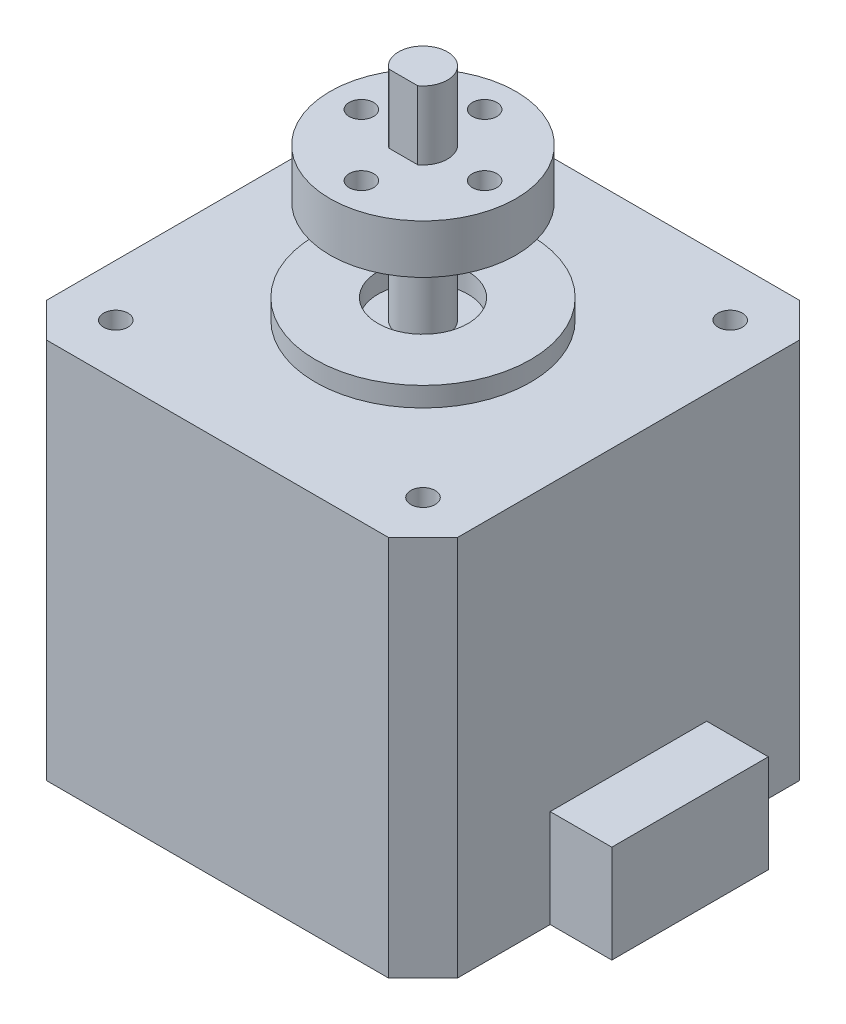
SolidWorks part; units mm, degrees
ref_plane "Plan de face" through (0, 0, 0) normal (0, 0, 1) x (1, 0, 0)
ref_plane "Plan de dessus" through (0, 0, 0) normal (0, 1, 0) x (1, 0, 0)
ref_plane "Plan de droite" through (0, 0, 0) normal (1, 0, 0) x (0, 0, -1)
sketch "Esquisse1" plane through (0, 0, 0) normal (0, 1, 0) x (1, 0, 0)
  line L0 (3.5355, 2.5496) -> (0, 6.0851)
  line L1 (0, 6.0851) -> (0, 41.014)
  line L2 (0, 41.014) -> (3.5355, 44.5496)
  line L3 (3.5355, 44.5496) -> (38.4645, 44.5496)
  line L4 (38.4645, 44.5496) -> (42, 41.014)
  line L5 (42, 41.014) -> (42, 6.0851)
  line L6 (42, 6.0851) -> (38.4645, 2.5496)
  line L7 (38.4645, 2.5496) -> (3.5355, 2.5496)
  dimension "D1" = 42
  dimension "D2" = 42
  dimension "D3" = 5
  dimension "D4" = 5
  dimension "D5" = 5
  dimension "D6" = 5
  dimension "D7" = 135
extrude "Boss.-Extru.1" add sketch "Esquisse1" along normal blind 39
sketch "Esquisse2" plane through (0, 39, 0) normal (0, 1, 0) x (1, 0, 0)
  line L1 (38.4645, 44.5496) -> (3.5355, 44.5496) construction
  line L2 (0, 41.014) -> (0, 6.0851) construction
  line L4 (42, 6.0851) -> (42, 41.014) construction
  line L5 (3.5355, 2.5496) -> (38.4645, 2.5496) construction
  circle A0 centre (5.3, 39.2496) radius 1.25
  circle A1 centre (36.7, 39.2496) radius 1.25
  circle A2 centre (36.7, 7.8496) radius 1.25
  circle A3 centre (5.3, 7.8496) radius 1.25
  dimension "D1" = 2.5
  dimension "D4" = 2.5
  dimension "D6" = 2.5
  dimension "D8" = 2.5
  dimension "D2" = 5.3
  dimension "D3" = 5.3
  dimension "D5" = 5.3
  dimension "D7" = 5.3
extrude "Enlèv. mat.-Extru.1" cut sketch "Esquisse2" against normal blind 39
sketch "Esquisse3" plane through (0, 39, 0) normal (0, 1, 0) x (1, 0, 0)
  line L0 (5.3, 7.8496) -> (36.7, 39.2496) construction
  line L1 (36.7, 7.8496) -> (5.3, 39.2496) construction
  circle A0 centre (21, 23.5496) radius 11
  circle A1 centre (21, 23.5496) radius 4.6
  dimension "D1" = 22
  dimension "D2" = 9.2
extrude "Boss.-Extru.2" add sketch "Esquisse3" along normal blind 2
sketch "Esquisse4" plane through (0, 39, 0) normal (0, 1, 0) x (1, 0, 0)
  circle A0 centre (21, 23.5496) radius 2.5
  dimension "D1" = 5
extrude "Boss.-Extru.3" add sketch "Esquisse4" along normal blind 22.5
ref_point "Point1"
ref_point "Point2"
ref_plane "Plan1" through (21, 0, 0) normal (1, 0, 0) x (0, 0, -1)
sketch "Esquisse5" plane through (21, 0, 0) normal (1, 0, 0) x (0, 0, -1)
  line L0 (23.5496, 61.5) -> (23.5496, 36.0808) construction
  line L1 (23.5496, 49.5) -> (14.0496, 49.5)
  line L2 (23.5496, 49.5) -> (23.5496, 54.5)
  line L3 (23.5496, 54.5) -> (14.0496, 54.5)
  line L4 (14.0496, 49.5) -> (14.0496, 54.5)
  line L6 (34.5496, 41) -> (12.5496, 41) construction
  dimension "D1" = 5
  dimension "D2" = 9.5
  dimension "D3" = 8.5
revolve "Révolution1" add sketch "Esquisse5" angle 360 about L0
sketch "Esquisse6" plane through (0, 54.5, 0) normal (0, 1, 0) x (1, 0, 0)
  line L0 (21, 23.5496) -> (33.6, 23.5496) construction
  line L1 (21, 23.5496) -> (21, 10.9496) construction
  line L2 (21, 23.5496) -> (8.4, 23.5496) construction
  line L3 (21, 23.5496) -> (21, 36.1496) construction
  circle A0 centre (27.3, 23.5496) radius 1.25
  circle A1 centre (21, 17.2496) radius 1.25
  circle A2 centre (21, 23.5496) radius 9.5 construction
  circle A3 centre (14.7, 23.5496) radius 1.25
  circle A4 centre (21, 29.8496) radius 1.25
  point P19 (21, 23.5496)
  dimension "D1" = 2.5
  dimension "D2" = 6.3
  dimension "D3" = 4
extrude "Enlèv. mat.-Extru.2" cut sketch "Esquisse6" against normal up to next
sketch "Esquisse8" plane through (0, 61.5, 0) normal (0, 1, 0) x (1, 0, 0)
  line L0 (22.4749, 21.531) -> (19.5251, 21.531)
  circle A0 centre (21, 23.5496) radius 2.5 construction
  arc A1 (22.4749, 21.531) -> (19.5251, 21.531) centre (21, 23.5496) cw
extrude "Enlèv. mat.-Extru.4" cut sketch "Esquisse8" against normal blind 7 contours L0 A1
sketch "Esquisse9" plane through (42, 0, 0) normal (1, 0, 0) x (0, 0, -1)
  line L0 (6.0851, 0) -> (41.014, 0) construction
  line L1 (15.549, 0) -> (31.549, 0)
  line L2 (15.549, 0) -> (15.549, 10)
  line L3 (15.549, 10) -> (31.549, 10)
  line L4 (31.549, 0) -> (31.549, 10)
  line L6 (41.014, 39) -> (41.014, 0) construction
  dimension "D1" = 16
  dimension "D2" = 10
  dimension "D3" = 9.465
extrude "Boss.-Extru.4" add sketch "Esquisse9" along normal blind 6.3
